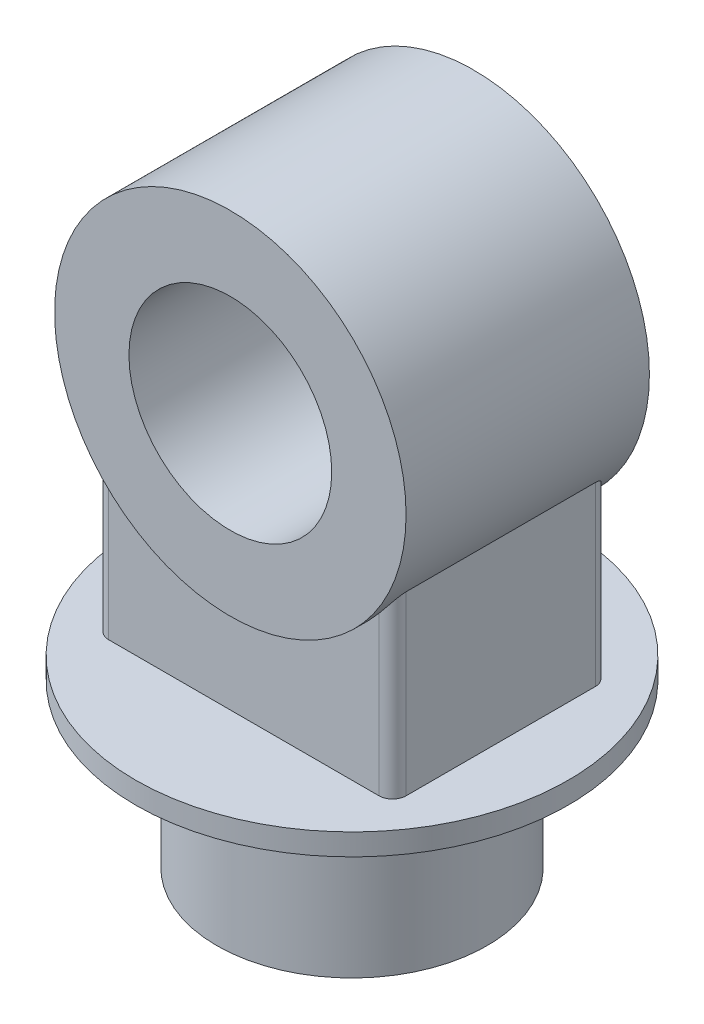
SolidWorks part; units mm, degrees
ref_plane "Front Plane" through (0, 0, 0) normal (0, 0, 1) x (1, 0, 0)
ref_plane "Top Plane" through (0, 0, 0) normal (0, 1, 0) x (1, 0, 0)
ref_plane "Right Plane" through (0, 0, 0) normal (1, 0, 0) x (0, 0, -1)
sketch "Sketch1" plane through (0, 0, 0) normal (0, 1, 0) x (1, 0, 0)
  circle A0 centre (0, 0) radius 2540
  dimension "D1" = 5080
extrude "Boss-Extrude1" add sketch "Sketch1" along normal blind 3048
sketch "Sketch2" plane through (0, 3048, 0) normal (0, 1, 0) x (1, 0, 0)
  circle A0 centre (0, 0) radius 4064
  dimension "D1" = 8128
extrude "Boss-Extrude2" add sketch "Sketch2" along normal blind 406.4
sketch "Sketch3" plane through (0, 0, 0) normal (0, 0, 1) x (1, 0, 0)
  line L0 (4064, 3454.4) -> (-4064, 3454.4) construction
  circle A0 centre (0, 8534.4) radius 1905
  circle A1 centre (0, 8534.4) radius 3302
  dimension "D1" = 3810
  dimension "D2" = 6604
  dimension "D3" = 5080
extrude "Boss-Extrude3" add sketch "Sketch3" along normal mid plane 4572 separate body
sketch "Sketch4" plane through (0, 3454.4, 0) normal (0, 1, 0) x (1, 0, 0)
  line L1 (2794, -2032) -> (-2794, -2032)
  line L2 (2794, -2032) -> (2794, 2032)
  line L3 (2794, 2032) -> (-2794, 2032)
  line L4 (-2794, -2032) -> (-2794, 2032)
  line L5 (2794, -2032) -> (-2794, 2032) construction
  line L6 (2794, 2032) -> (-2794, -2032) construction
  point P0 (0, 0)
  dimension "D1" = 4064
  dimension "D2" = 5588
extrude "Boss-Extrude4" add sketch "Sketch4" along normal up to next
fillet "Fillet1" radius 254 4 edges at (2794, 5114.5182, -2032) (-2794, 5114.5182, -2032) (2794, 5114.5182, 2032) (-2794, 5114.5182, 2032)
